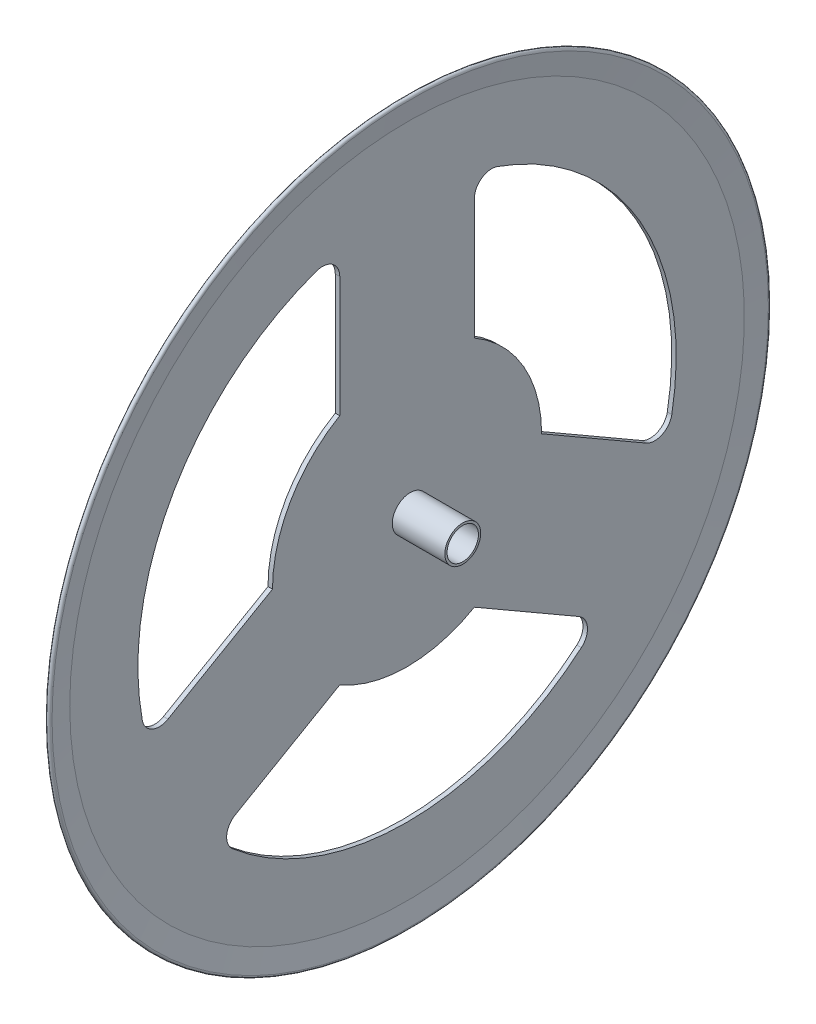
SolidWorks part; units mm, degrees
ref_plane "Front Plane" through (0, 0, 0) normal (0, 0, 1) x (1, 0, 0)
ref_plane "Top Plane" through (0, 0, 0) normal (0, 1, 0) x (1, 0, 0)
ref_plane "Right Plane" through (0, 0, 0) normal (1, 0, 0) x (0, 0, -1)
sketch "Sketch1" plane through (0, 0, 0) normal (0, 0, 1) x (1, 0, 0)
  line L0 (0, 0) -> (-75.2862, 0) construction
  line L1 (-22.4009, 0) -> (-22.4009, 75.2707)
  line L2 (-22.4009, 75.2707) -> (-21.6835, 80)
  line L3 (-21.4009, 0) -> (-21.4009, 75.1953)
  line L4 (-21.4009, 75.1953) -> (-20.6948, 79.85)
  line L5 (-22.4009, 0) -> (-21.4009, 0)
  arc A1 (-21.6835, 80) -> (-20.6948, 79.85) centre (-21.1892, 79.925) cw
  dimension "D1" = 160
  dimension "D2" = 1
revolve "Revolve1" add sketch "Sketch1" angle 360 about L5
sketch "Sketch2" plane through (-21.4009, 0, 0) normal (1, 0, 0) x (0, 0, -1)
  line L0 (0, 0) -> (0, 96.337) construction
  line L1 (-15, 52.8705) -> (-15, 25.9808)
  line L2 (15, 52.8705) -> (15, 25.9808)
  line L3 (53.2872, -13.4449) -> (30, 0)
  line L4 (38.2872, -39.4256) -> (15, -25.9808)
  line L5 (-38.2872, -39.4256) -> (-15, -25.9808)
  line L6 (-53.2872, -13.4449) -> (-30, 0)
  circle A0 centre (0, 0) radius 30
  arc A1 (-20.1635, 56.5105) -> (20.1635, 56.5105) centre (0, 0) ccw
  arc A2 (-20.1635, 56.5105) -> (-15, 52.8705) centre (-18.8648, 52.8705) cw
  arc A3 (20.1635, 56.5105) -> (15, 52.8705) centre (18.8648, 52.8705) ccw
  arc A4 (59.0213, -10.7931) -> (53.2872, -13.4449) centre (55.2195, -10.0979) cw
  arc A5 (38.8577, -45.7174) -> (38.2872, -39.4256) centre (36.3548, -42.7726) ccw
  arc A6 (-38.8577, -45.7174) -> (-38.2872, -39.4256) centre (-36.3548, -42.7726) cw
  arc A7 (-59.0213, -10.7931) -> (-53.2872, -13.4449) centre (-55.2195, -10.0979) ccw
  dimension "D1" = 120
  dimension "D2" = 60
  dimension "D3" = 3
extrude "Cut-Extrude1" cut sketch "Sketch2" against normal through all contours A1 A7 L6 A0 L1 A2 | A6 A1 A5 L4 A0 L5 | A4 A1 A3 L2 A0 L3
sketch "Sketch4" plane through (0, 0, 0) normal (0, 0, 1) x (1, 0, 0)
  line L0 (-20.6948, 0) -> (4.3387, 0) construction
  line L1 (-20.6948, 79.85) -> (-20.6948, -79.85) construction
  line L3 (-18.9827, 4) -> (-8.9827, 4)
  line L4 (-8.9827, 4) -> (-8.9827, 0)
  line L5 (-8.9827, 0) -> (-20.6948, 0)
  line L6 (-20.6948, 0) -> (-20.6948, 4)
  line L7 (-18.9827, 4) -> (-20.6948, 4)
  dimension "D1" = 10
  dimension "D2" = 8
revolve "Revolve2" add sketch "Sketch4" angle 360 about L0
sketch "Sketch5" plane through (-8.9827, 0, 0) normal (1, 0, 0) x (0, 0, -1)
  circle A0 centre (0, 0) radius 3.5
  dimension "D1" = 7
extrude "Cut-Extrude2" cut sketch "Sketch5" against normal blind 8 contours A0
